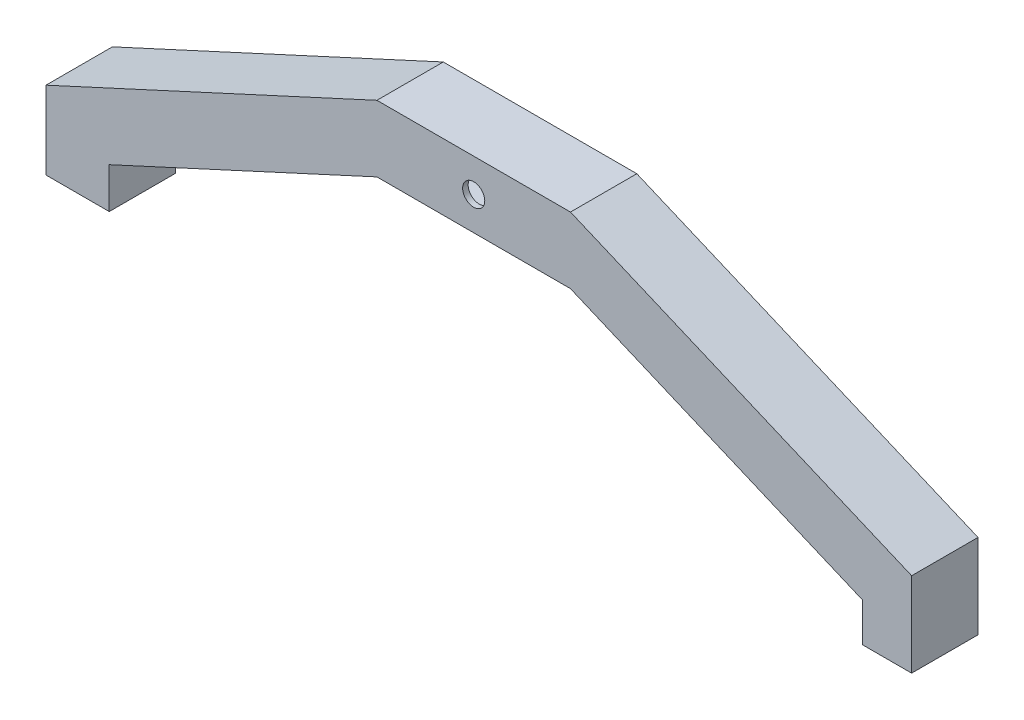
SolidWorks part; units mm, degrees
material "1060 Alloy"
ref_plane "Front Plane" through (0, 0, 0) normal (0, 0, 1) x (1, 0, 0)
ref_plane "Top Plane" through (0, 0, 0) normal (0, 1, 0) x (1, 0, 0)
ref_plane "Right Plane" through (0, 0, 0) normal (1, 0, 0) x (0, 0, -1)
sketch "Sketch1" plane through (0, 0, 0) normal (0, 0, 1) x (1, 0, 0)
  line L0 (-17.5, 6) -> (-77.3429, -21.55)
  line L1 (-17.5, 6) -> (17.5, 6)
  line L3 (-17.5, -6) -> (17.5, -6)
  line L5 (17.5, -6) -> (70.2639, -28.3286)
  line L6 (-77.3429, -35.63) -> (-65.9063, -35.63)
  line L8 (70.2639, -28.3286) -> (70.2639, -35.3685)
  line L9 (70.2639, -35.3685) -> (79.195, -35.3685)
  line L10 (-77.3429, -35.63) -> (-65.9063, -35.63) construction
  line L11 (-65.9063, -28.2849) -> (-17.5, -6)
  line L14 (-74.9005, -35.63) -> (-65.9063, -35.63)
  line L17 (-77.3429, -21.55) -> (-77.3429, -35.63)
  line L18 (-77.3429, -35.63) -> (-65.9063, -35.63)
  line L19 (-65.9063, -28.2849) -> (-65.9063, -35.63)
  line L21 (17.5, 6) -> (79.195, -20.1081)
  line L22 (79.195, -35.3685) -> (79.195, -20.1081)
  circle A0 centre (88.9387, -52.443) radius 30.5 construction
  point P0 (0, 0)
  point P13 (0, -35.63)
  dimension "D1" = 35
  dimension "D2" = 12
  dimension "D3" = 65.88
  dimension "D4" = 155.28
extrude "Boss-Extrude1" add sketch "Sketch1" along normal blind 12
shell "Shell1" thickness 1
sketch "Sketch2" plane through (0, -35.63, 0) normal (0, -1, 0) x (1, 0, 0)
  line L0 (95.1571, 12) -> (95.1571, 0) construction
  line L1 (84.1571, 11.1014) -> (94.1571, 11.1014)
  line L2 (84.1571, 11.1014) -> (84.1571, 1.1014)
  line L3 (84.1571, 1.1014) -> (94.1571, 1.1014)
  line L4 (94.1571, 11.1014) -> (94.1571, 1.1014)
  line L5 (84.1571, 11.1014) -> (94.1571, 1.1014) construction
  line L6 (84.1571, 1.1014) -> (94.1571, 11.1014) construction
  point P0 (89.1571, 6.1014)
  dimension "D1" = 10
  dimension "D2" = 10
  dimension "D3" = 1
extrude "Cut-Extrude1" cut sketch "Sketch2" against normal blind 12
sketch "Sketch3" plane through (0, 0, 12) normal (0, 0, 1) x (1, 0, 0)
  line L0 (-17.5, 6) -> (17.5, 6) construction
  circle A0 centre (0, 0) radius 2
  dimension "D1" = 4
  dimension "D2" = 6
  dimension "D3" = 17.5
extrude "Cut-Extrude2" cut sketch "Sketch3" against normal blind 12
sketch "Sketch5" plane through (0, -35.63, 0) normal (0, -1, 0) x (1, 0, 0)
  line L0 (82.9391, 0) -> (83.1571, 0)
  line L1 (82.9391, 12) -> (95.1571, 12)
  line L2 (82.9391, 12) -> (82.9391, 0)
  line L4 (95.1571, 12) -> (95.1571, 0)
  line L5 (95.1571, 12) -> (83.1571, 12)
  line L6 (95.1571, 12) -> (95.1571, 0)
  line L7 (95.1571, 0) -> (83.1571, 0)
  line L8 (83.1571, 12) -> (83.1571, 0)
  dimension "D1" = 12
  dimension "D2" = 12
extrude "Cut-Extrude3" cut sketch "Sketch5" against normal up to surface (1.9375 mm away)
